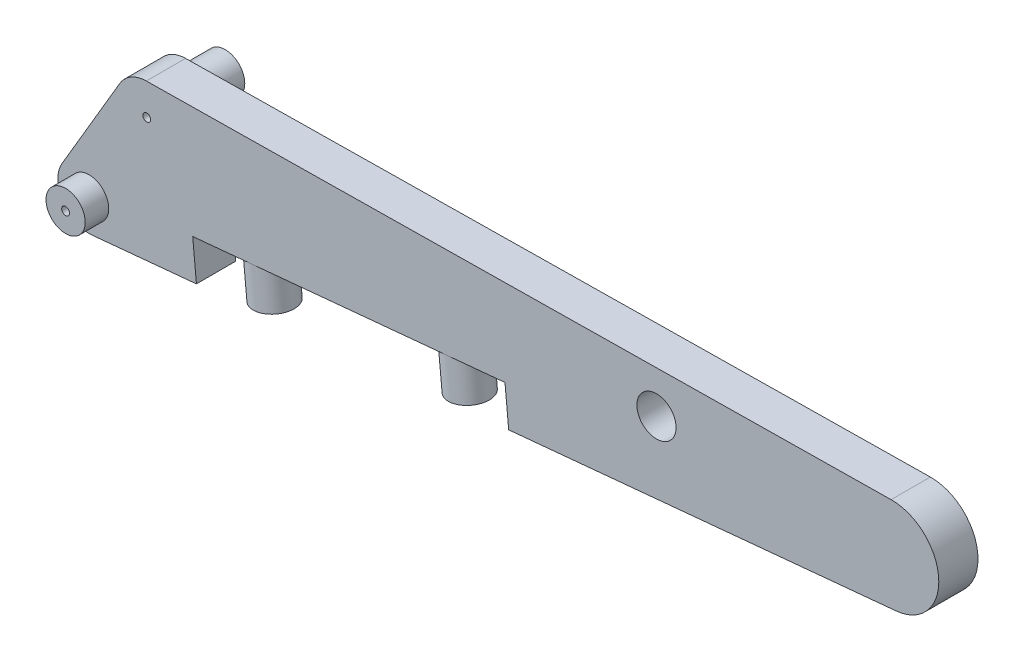
SolidWorks part; units mm, degrees
material "ABS"
ref_plane "Front Plane" through (0, 0, 0) normal (0, 0, 1) x (1, 0, 0)
ref_plane "Top Plane" through (0, 0, 0) normal (0, 1, 0) x (1, 0, 0)
ref_plane "Right Plane" through (0, 0, 0) normal (1, 0, 0) x (0, 0, -1)
sketch "Sketch2" plane through (0, 0, 0) normal (0, 0, 1) x (1, 0, 0)
  line L0 (-7.3485, -12.5) -> (0, 0)
  line L1 (0, 0) -> (95, -0.7468)
  dimension "D1" = 95
  dimension "D2" = 14.5
  dimension "D3" = 120
sketch "Sketch3" plane through (0, 0, 0) normal (0, 0, 1) x (1, 0, 0)
  line L0 (-10.7968, -10.4728) -> (-3.4483, 2.0272)
  line L1 (-0.0528, 3.9997) -> (94.9208, 5.2527)
  line L2 (95.5687, -6.7198) -> (-6.9694, -16.482)
  circle A0 centre (-7.3485, -12.5) radius 2.5
  arc A1 (-10.7968, -10.4728) -> (-6.9694, -16.482) centre (-7.3485, -12.5) ccw
  circle A2 centre (0, 0) radius 2.5
  arc A3 (-0.0528, 3.9997) -> (-3.4483, 2.0272) centre (0, 0) ccw
  arc A4 (95.5687, -6.7198) -> (94.9208, 5.2527) centre (95, -0.7468) ccw
  dimension "D1" = 5
  dimension "D2" = 8
  dimension "D3" = 5
  dimension "D4" = 8
  dimension "D5" = 12
extrude "Boss-Extrude1" add sketch "Sketch3" along normal blind 5
sketch "Sketch4" plane through (0, 0, 5) normal (0, 0, 1) x (1, 0, 0)
  circle A0 centre (0, 0) radius 2.5
  circle A1 centre (0, 0) radius 0.5
  dimension "D1" = 1
  dimension "D2" = 5
extrude "Boss-Extrude2" add sketch "Sketch4" against normal blind 10
sketch "Sketch5" plane through (0, 0, 0) normal (0, 0, -1) x (-1, 0, 0)
  circle A0 centre (7.3485, -12.5) radius 2.5
  circle A1 centre (7.3485, -12.5) radius 0.5
  dimension "D1" = 1
  dimension "D2" = 5
extrude "Boss-Extrude3" add sketch "Sketch5" against normal blind 8
sketch "Sketch6" plane through (0, 0, 0) normal (0, 0, -1) x (-1, 0, 0)
  line L0 (0, 0) -> (-95, -0.7468) construction
  circle A1 centre (-65, -0.511) radius 2.5
  dimension "D1" = 5
  dimension "D2" = 30
extrude "Cut-Extrude1" cut sketch "Sketch6" against normal blind 5
sketch "Sketch7" plane through (0, 0, 0) normal (0, 0, -1) x (-1, 0, 0)
  line L0 (-46.1534, -11.4244) -> (-6.3335, -15.2155)
  line L1 (-46.1534, -11.4244) -> (-45.6774, -6.4244)
  line L2 (-6.3335, -15.2155) -> (-5.8574, -10.2155)
  line L3 (-45.6774, -6.4244) -> (-5.8574, -10.2155)
  line L4 (6.9694, -16.482) -> (-95.5687, -6.7198) construction
  dimension "D1" = 50
  dimension "D2" = 5
  dimension "D3" = 40
extrude "Cut-Extrude2" cut sketch "Sketch7" against normal blind 5
sketch "Sketch8" plane through (1.0165, -10.6764, 0) normal (0.0948, -0.9955, 0) x (0.9955, 0.0948, 0)
  line L0 (4.8629, 0) -> (44.8629, 0) construction
  line L1 (44.8629, 5) -> (44.8629, 0) construction
  line L2 (4.8629, 5) -> (4.8629, 0) construction
  circle A0 centre (12.3629, 2.5) radius 2.5
  circle A1 centre (12.3629, 2.5) radius 0.5
  circle A2 centre (37.3629, 2.5) radius 0.5
  circle A3 centre (37.3629, 2.5) radius 2.5
  dimension "D1" = 5
  dimension "D2" = 1
  dimension "D6" = 1
  dimension "D7" = 5
  dimension "D3" = 2.5
  dimension "D4" = 7.5
  dimension "D5" = 2.5
  dimension "D8" = 7.5
extrude "Boss-Extrude4" add sketch "Sketch8" along normal blind 5
